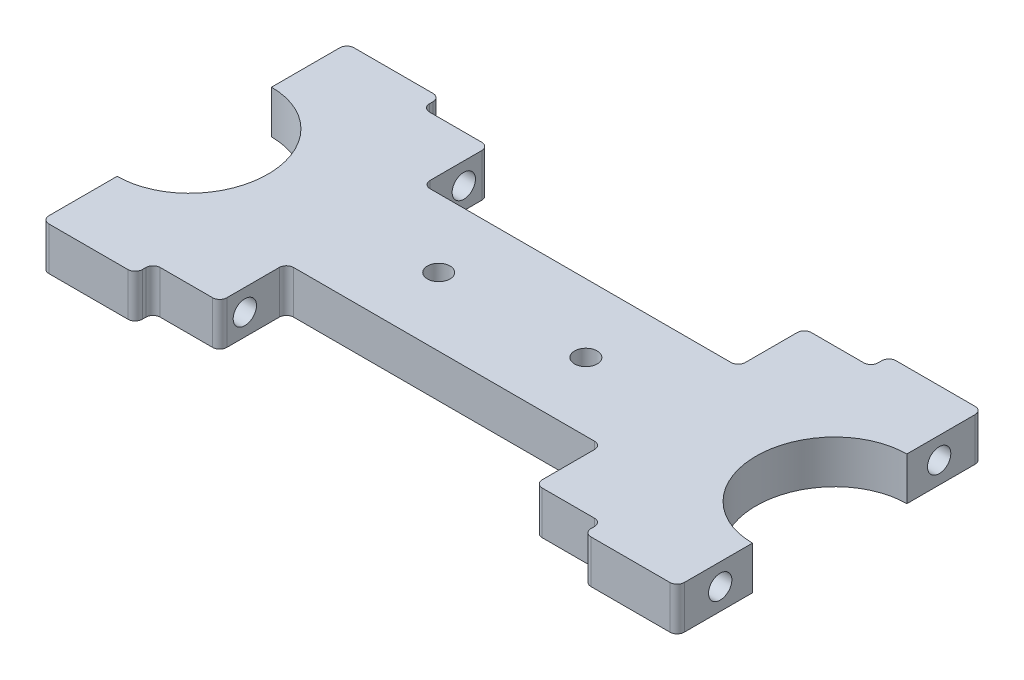
SolidWorks part; units mm, degrees
ref_plane "前基準面" through (0, 0, 0) normal (0, 0, 1) x (1, 0, 0)
ref_plane "上基準面" through (0, 0, 0) normal (0, 1, 0) x (1, 0, 0)
ref_plane "右基準面" through (0, 0, 0) normal (1, 0, 0) x (0, 0, -1)
sketch "草圖1" plane through (0, 0, 0) normal (0, 1, 0) x (1, 0, 0)
  line L0 (133.4244, -23.5) -> (45.5756, -23.5)
  line L2 (133.4244, -5.0847) -> (152, -5.0847)
  line L3 (178, -85.0847) -> (152, -85.0847)
  line L4 (152, -80.0847) -> (152, -85.0847)
  line L5 (178, -85.0847) -> (178, -64.0847)
  line L6 (133.4244, -80.0847) -> (152, -80.0847)
  line L7 (133.4244, -61.5) -> (45.5756, -61.5)
  line L8 (89.5, 81.4346) -> (89.5, -132.995) construction
  line L11 (-41.386, -42.5847) -> (220.386, -42.5847) construction
  line L12 (178, -0.0847) -> (178, -21.0847)
  line L16 (152, -5.0847) -> (152, -0.0847)
  line L18 (178, -0.0847) -> (152, -0.0847)
  line L22 (1, -0.0847) -> (27, -0.0847)
  line L23 (27, -5.0847) -> (27, -0.0847)
  line L24 (1, -0.0847) -> (1, -21.0847)
  line L25 (45.5756, -80.0847) -> (27, -80.0847)
  line L26 (1, -85.0847) -> (1, -64.0847)
  line L27 (27, -80.0847) -> (27, -85.0847)
  line L28 (1, -85.0847) -> (27, -85.0847)
  line L29 (45.5756, -5.0847) -> (27, -5.0847)
  line L30 (133.4244, -61.5) -> (133.4244, -80.0847)
  line L32 (133.4244, -23.5) -> (133.4244, -5.0847)
  line L34 (45.5756, -23.5) -> (45.5756, -5.0847)
  line L36 (45.5756, -61.5) -> (45.5756, -80.0847)
  ellipse E0 centre (178, -42.5847) end of major axis (178, -21.0847) minor radius 20.5 (178, -21.0847) -> (178, -64.0847) ccw
  ellipse E1 centre (1, -42.5847) end of major axis (1, -21.0847) minor radius 20.5 (1, -21.0847) -> (1, -64.0847) cw
  point P24 (89.5, -68.0444)
  point P25 (89.5, -23.5)
  point P26 (89.5, -42.5847)
  point P33 (89.5, -23.5)
  point P36 (89.5, -61.5)
  point P44 (89.5, -61.5)
  point P48 (89.5, -23.5)
  dimension "D3" = 41
  dimension "D4" = 88.5
  dimension "D1" = 85
  dimension "D2" = 21.5
  dimension "D5" = 26
extrude "填料-伸長1" add sketch "草圖1" along normal blind 12
sketch "草圖2" plane through (178, 0, 0) normal (1, 0, 0) x (0, 0, -1)
  line L0 (-0.0847, 12) -> (-0.0847, 0) construction
  line L1 (-33.2434, 6) -> (5.252, 6) construction
  line L2 (-21.0847, 0) -> (-0.0847, 0) construction
  line L3 (-21.0847, 12) -> (-64.0847, 12) construction
  line L4 (-21.0847, 12) -> (-0.0847, 12) construction
  line L6 (-42.5847, 12) -> (-42.5847, -11.269) construction
  circle A2 centre (-12.0847, 6) radius 3.25
  circle A3 centre (-73.0847, 6) radius 3.25
  dimension "D2" = 12
  dimension "D1" = 6.5
extrude "除料-伸長3" cut sketch "草圖2" against normal through all
fillet "圓角1" radius 2 16 edges at (152, 6, 0.0847) (152, 6, 5.0847) (133.4244, 6, 5.0847) (133.4244, 6, 23.5) (27, 6, 0.0847) (27, 6, 5.0847) (45.5756, 6, 5.0847) (45.5756, 6, 23.5) (152, 6, 85.0847) (152, 6, 80.0847) (133.4244, 6, 80.0847) (133.4244, 6, 61.5) (45.5756, 6, 61.5) (45.5756, 6, 80.0847) (27, 6, 80.0847) (27, 6, 85.0847)
fillet "圓角2" radius 2 4 edges at (1, 6, 0.0847) (1, 6, 85.0847) (178, 6, 0.0847) (178, 6, 85.0847)
sketch "草圖3" plane through (0, 12, 0) normal (0, 1, 0) x (1, 0, 0)
  line L0 (178, -21.0847) -> (178, -2.0847) construction
  line L1 (89.5, -23.5) -> (89.5, -75.6699) construction
  line L2 (131.4244, -23.5) -> (47.5756, -23.5) construction
  line L3 (157.5002, -42.5) -> (194.4763, -42.5) construction
  line L4 (47.5756, -61.5) -> (131.4244, -61.5) construction
  circle A0 centre (110, -42.5) radius 3.15
  circle A1 centre (69, -42.5) radius 3.15
  ellipse E0 centre (178, -42.5847) end of major axis (178, -21.0847) minor radius 20.5 (178, -21.0847) -> (178, -64.0847) ccw construction
  dimension "D2" = 6.3
  dimension "D1" = 68
extrude "除料-伸長4" cut sketch "草圖3" against normal through all
